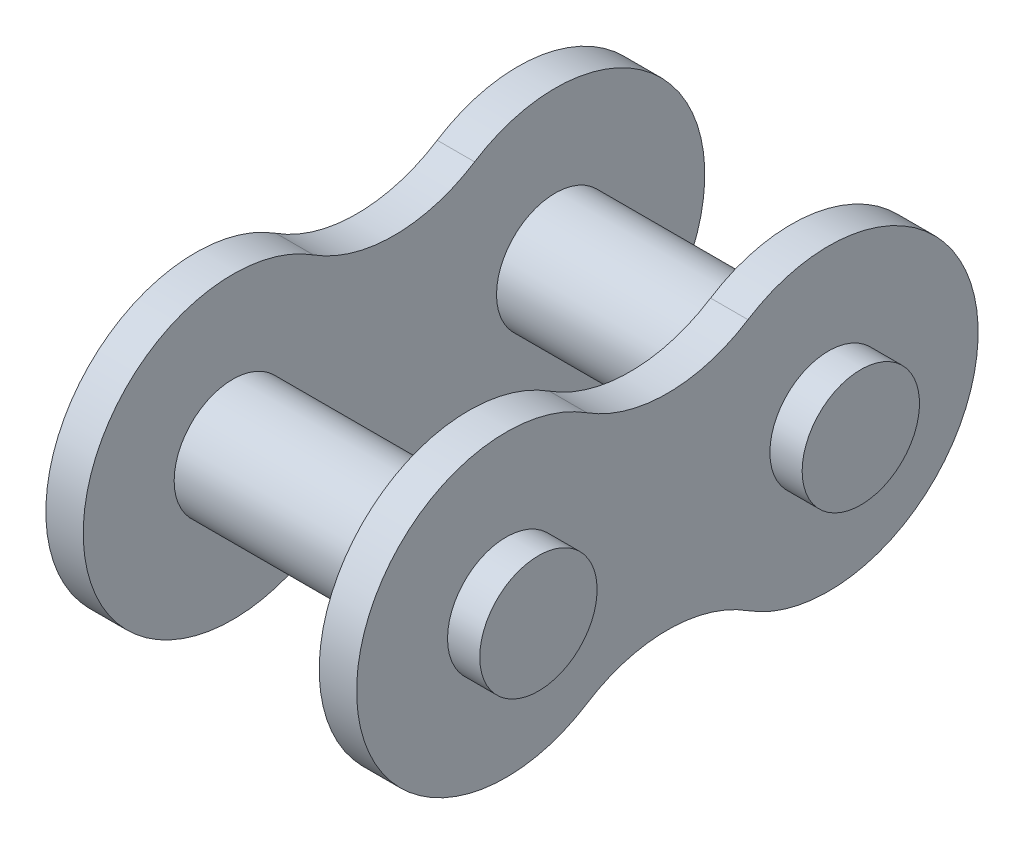
SolidWorks part; units mm, degrees
ref_plane "Front Plane" through (0, 0, 0) normal (0, 0, 1) x (1, 0, 0)
ref_plane "Top Plane" through (0, 0, 0) normal (0, 1, 0) x (1, 0, 0)
ref_plane "Right Plane" through (0, 0, 0) normal (1, 0, 0) x (0, 0, -1)
sketch "Sketch1" plane through (0, 0, 0) normal (1, 0, 0) x (0, 0, -1)
  line L0 (0, 0) -> (6.35, 0) construction
  arc A0 (1.5875, 2.4822) -> (1.5875, -2.4822) centre (0, 0) ccw
  arc A1 (4.7625, -2.4822) -> (4.7625, 2.4822) centre (6.35, 0) ccw
  arc A4 (1.5875, 2.4822) -> (4.7625, 2.4822) centre (3.175, 4.9643) ccw
  arc A5 (1.5875, -2.4822) -> (4.7625, -2.4822) centre (3.175, -4.9643) cw
  point P9 (3.175, 0)
  point P10 (0, 0)
  point P11 (3.175, 4.9334)
  dimension "D1" = 5.8928
  dimension "D2" = 6.35
extrude "Boss-Extrude1" add sketch "Sketch1" along normal blind 0.7366
sketch "Sketch2" plane through (0.7366, 0, 0) normal (1, 0, 0) x (0, 0, -1)
  circle A0 centre (0, 0) radius 1.1557
  circle A2 centre (6.35, 0) radius 1.1557
  point P3 (6.35, 0)
  point P7 (0, -0.0878)
  point P8 (0, 0)
  dimension "D1" = 2.3114
extrude "Boss-Extrude2" add sketch "Sketch2" along normal blind 4.6482
ref_plane "Plane1" through (3.0607, 0, 0) normal (1, 0, 0) x (0, 0, -1)
sketch "Sketch3" plane through (0, 0, 0) normal (-1, 0, 0) x (0, 0, 1)
  circle A0 centre (0, 0) radius 1.1557
  circle A1 centre (-6.35, 0) radius 1.1557
  circle A2 centre (0, 0) radius 1.1557 construction
extrude "Boss-Extrude3" add sketch "Sketch3" along normal blind 0.635
mirror "Mirror1" about plane through (3.0607, 0, 0) normal (1, 0, 0) of "Boss-Extrude3", "Boss-Extrude1"
